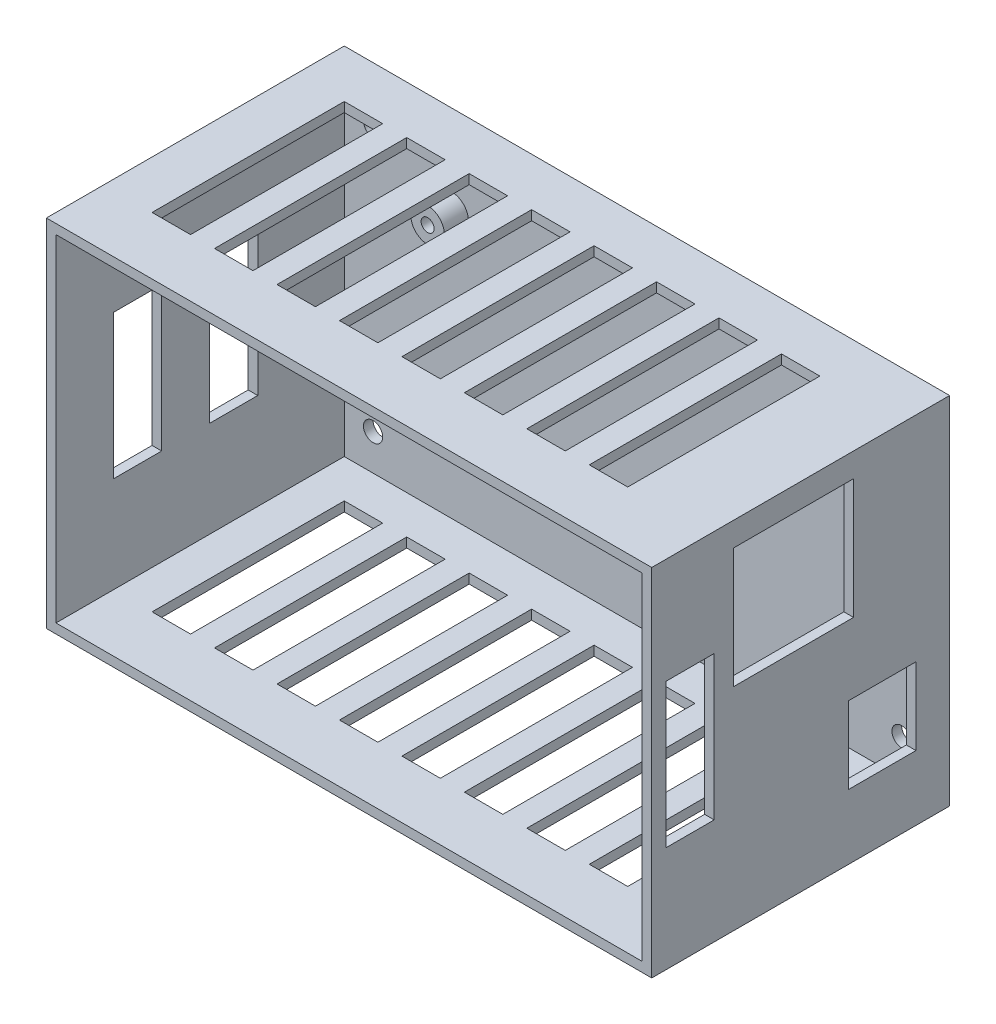
SolidWorks part; units mm, degrees
ref_plane "Plano frontal" through (0, 0, 0) normal (0, 0, 1) x (1, 0, 0)
ref_plane "Plano superior" through (0, 0, 0) normal (0, 1, 0) x (1, 0, 0)
ref_plane "Plano direito" through (0, 0, 0) normal (1, 0, 0) x (0, 0, -1)
sketch "Esboço1" plane through (0, 0, 0) normal (0, 0, 1) x (1, 0, 0)
  line L0 (-63, 37) -> (63, 37)
  line L1 (-61, 35) -> (61, 35)
  line L2 (-61, 35) -> (-61, -35)
  line L3 (-61, -35) -> (61, -35)
  line L4 (61, 35) -> (61, -35)
  line L5 (-61, 35) -> (61, -35) construction
  line L6 (-61, -35) -> (61, 35) construction
  line L7 (63, 37) -> (63, -37)
  line L8 (-63, -37) -> (63, -37)
  line L9 (-63, 37) -> (-63, -37)
  point P0 (0, 0)
  dimension "D2" = 122
  dimension "D3" = 70
  dimension "D1" = 2
extrude "Ressalto-extrusão1" add sketch "Esboço1" along normal blind 60
sketch "Esboço2" plane through (0, 0, 0) normal (0, 0, -1) x (-1, 0, 0)
  line L0 (-63, -37) -> (-63, 37) construction
  line L1 (63, -37) -> (-63, -37) construction
  line L2 (-63, 37) -> (63, 37) construction
  line L3 (63, 37) -> (63, -37) construction
  line L4 (-63, -37) -> (-63, 37)
  line L5 (63, -37) -> (-63, -37)
  line L6 (-63, 37) -> (63, 37)
  line L7 (63, 37) -> (63, -37)
  line L8 (55, 27.5) -> (-55, 27.5) construction
  line L9 (-55, 27.5) -> (-55, -27.5) construction
  line L10 (-55, -27.5) -> (55, -27.5) construction
  line L11 (55, -27.5) -> (55, 27.5) construction
  circle A0 centre (-55, -27.5) radius 2
  circle A1 centre (55, -27.5) radius 2
  circle A2 centre (55, 27.5) radius 2
  circle A3 centre (-55, 27.5) radius 2
  point P12 (0, 27.5)
  point P13 (0, 37)
  point P14 (-55, 0)
  point P15 (-63, 0)
  point P16 (0, 0)
  dimension "D1" = 4
  dimension "D2" = 110
  dimension "D3" = 55
extrude "Ressalto-extrusão2" add sketch "Esboço2" along normal blind 2
sketch "Esboço3" plane through (63, 0, 0) normal (1, 0, 0) x (0, 0, -1)
  line L0 (-60, -37) -> (2, -37) construction
  line L1 (-43, 32) -> (-18, 32)
  line L2 (-43, 32) -> (-43, 7)
  line L3 (-43, 7) -> (-18, 7)
  line L4 (-18, 32) -> (-18, 7)
  line L5 (-19, -7.5) -> (-5, -7.5)
  line L6 (-19, -7.5) -> (-19, -23.5)
  line L7 (-19, -23.5) -> (-5, -23.5)
  line L8 (-5, -7.5) -> (-5, -23.5)
  line L9 (2, 37) -> (2, -37) construction
  line L10 (-60, 37) -> (2, 37) construction
  line L11 (-60, -37) -> (-60, 37) construction
  line L12 (-57, 15) -> (-47, 15)
  line L13 (-57, 15) -> (-57, -15)
  line L14 (-57, -15) -> (-47, -15)
  line L15 (-47, 15) -> (-47, -15)
  line L16 (-57, 15) -> (-47, -15) construction
  line L17 (-57, -15) -> (-47, 15) construction
  point P14 (-52, 0)
  point P23 (-60, 0)
  dimension "D1" = 16
  dimension "D2" = 14
  dimension "D3" = 13.5
  dimension "D4" = 7
  dimension "D5" = 25
  dimension "D6" = 25
  dimension "D7" = 5
  dimension "D8" = 20
  dimension "D9" = 8
  dimension "D10" = 30
  dimension "D11" = 10
extrude "Corte-extrusão1" cut sketch "Esboço3" against normal blind 10
sketch "Esboço6" plane through (0, -37, 0) normal (0, -1, 0) x (1, 0, 0)
  line L0 (63, -2) -> (-63, -2) construction
  line L1 (-53, 48) -> (-45, 48)
  line L2 (-53, 48) -> (-53, 8)
  line L3 (-53, 8) -> (-45, 8)
  line L4 (-45, 48) -> (-45, 8)
  line L5 (-63, 60) -> (-63, -2) construction
  line L6 (-40, 48) -> (-32, 48)
  line L7 (-40, 48) -> (-40, 8)
  line L8 (-40, 8) -> (-32, 8)
  line L9 (-32, 48) -> (-32, 8)
  line L10 (-27, 48) -> (-19, 48)
  line L11 (-27, 48) -> (-27, 8)
  line L12 (-27, 8) -> (-19, 8)
  line L13 (-19, 48) -> (-19, 8)
  line L14 (-14, 48) -> (-6, 48)
  line L15 (-14, 48) -> (-14, 8)
  line L16 (-14, 8) -> (-6, 8)
  line L17 (-6, 48) -> (-6, 8)
  line L18 (-1, 48) -> (7, 48)
  line L19 (-1, 48) -> (-1, 8)
  line L20 (-1, 8) -> (7, 8)
  line L21 (7, 48) -> (7, 8)
  line L22 (12, 48) -> (20, 48)
  line L23 (12, 48) -> (12, 8)
  line L24 (12, 8) -> (20, 8)
  line L25 (20, 48) -> (20, 8)
  line L26 (25, 48) -> (33, 48)
  line L27 (25, 48) -> (25, 8)
  line L28 (25, 8) -> (33, 8)
  line L29 (33, 48) -> (33, 8)
  line L30 (38, 48) -> (46, 48)
  line L31 (38, 48) -> (38, 8)
  line L32 (38, 8) -> (46, 8)
  line L33 (46, 48) -> (46, 8)
  dimension "D1" = 8
  dimension "D2" = 40
  dimension "D3" = 10
  dimension "D4" = 10
  dimension "D5" = 8
extrude "Corte-extrusão2" cut sketch "Esboço6" against normal through all
sketch "Esboço7" plane through (-63, 0, 0) normal (-1, 0, 0) x (0, 0, 1)
  line L0 (-2, -37) -> (-2, 37) construction
  line L1 (48, 15) -> (38, 15)
  line L2 (48, 15) -> (48, -15)
  line L3 (48, -15) -> (38, -15)
  line L4 (38, 15) -> (38, -15)
  line L5 (48, 15) -> (38, -15) construction
  line L6 (48, -15) -> (38, 15) construction
  line L7 (28, 15) -> (18, 15)
  line L8 (28, 15) -> (28, -15)
  line L9 (28, -15) -> (18, -15)
  line L10 (18, 15) -> (18, -15)
  line L11 (28, 15) -> (18, -15) construction
  line L12 (28, -15) -> (18, 15) construction
  point P0 (43, 0)
  point P5 (23, 0)
  dimension "D1" = 10
  dimension "D2" = 30
  dimension "D3" = 10
  dimension "D4" = 20
extrude "Corte-extrusão3" cut sketch "Esboço7" against normal blind 12
sketch "Esboço8" plane through (0, 0, 0) normal (0, 0, 1) x (1, 0, 0)
  circle A0 centre (40.2574, -26.4452) radius 3.5
  circle A1 centre (40.2574, -26.4452) radius 1.35
  circle A2 centre (-38.65, 20.4) radius 3.5
  circle A3 centre (-38.65, 20.4) radius 1.35
  circle A4 centre (41.55, 20.6) radius 1.35
  circle A5 centre (41.55, 20.6) radius 1.35
  circle A6 centre (41.55, 20.6) radius 3.5
  dimension "D1" = 7
  dimension "D2" = 2.7
extrude "Ressalto-extrusão3" add sketch "Esboço8" along normal blind 5 contours A2 A3 | A0 A1 | A6 A4
